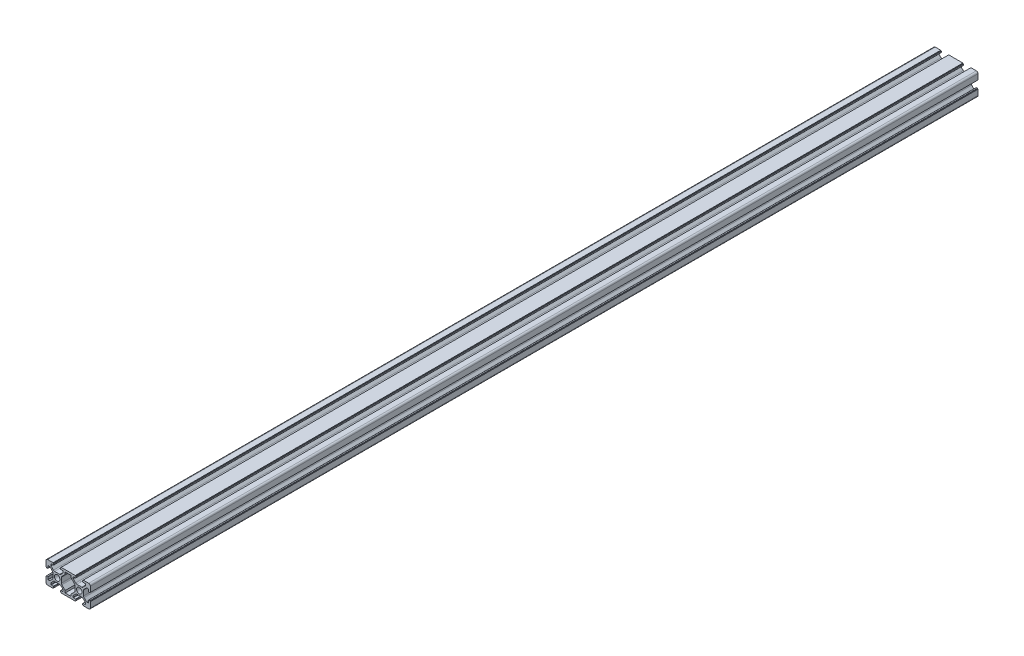
SolidWorks part; units mm, degrees
ref_plane "前视基准面" through (0, 0, 0) normal (0, 0, 1) x (1, 0, 0)
ref_plane "上视基准面" through (0, 0, 0) normal (0, 1, 0) x (1, 0, 0)
ref_plane "右视基准面" through (0, 0, 0) normal (1, 0, 0) x (0, 0, -1)
sketch "草图1" plane through (0, 0, 0) normal (0, 0, 1) x (1, 0, 0)
  line L0 (-1.9716, -6.6942) -> (-4.9322, -3.7335)
  line L1 (-5.3716, -2.6729) -> (-5.3716, 1.7645)
  line L2 (-4.9322, 2.8251) -> (-1.9716, 5.7858)
  line L3 (-0.7716, 9.5458) -> (-5.6716, 9.5458)
  line L4 (-5.6716, 9.5458) -> (-5.6716, 9.2458)
  line L5 (-5.8716, 9.0458) -> (-6.1716, 9.0458)
  line L6 (-6.1716, 9.0458) -> (-6.1716, 8.0458)
  line L7 (-5.8716, 7.7458) -> (-4.0716, 7.7458)
  line L8 (-3.7716, 7.4458) -> (-3.7716, 6.1058)
  line L9 (-3.7716, 6.1058) -> (-5.9922, 3.8851)
  line L10 (-7.0529, 3.4458) -> (-11.4903, 3.4458)
  line L11 (-12.5509, 3.8851) -> (-14.7716, 6.1058)
  line L12 (-14.7716, 6.1058) -> (-14.7716, 7.4458)
  line L13 (-14.4716, 7.7458) -> (-12.6716, 7.7458)
  line L14 (-12.3716, 8.0458) -> (-12.3716, 9.0458)
  line L15 (-12.3716, 9.0458) -> (-12.6716, 9.0458)
  line L16 (-12.8716, 9.2458) -> (-12.8716, 9.5458)
  line L17 (-12.8716, 9.5458) -> (-17.7716, 9.5458)
  line L18 (-19.2716, 8.0458) -> (-19.2716, 3.1458)
  line L19 (-19.2716, 3.1458) -> (-18.9716, 3.1458)
  line L20 (-18.7716, 2.9458) -> (-18.7716, 2.6458)
  line L21 (-18.7716, 2.6458) -> (-17.7716, 2.6458)
  line L22 (-17.4716, 2.9458) -> (-17.4716, 4.7458)
  line L23 (-17.1716, 5.0458) -> (-15.8316, 5.0458)
  line L24 (-15.8316, 5.0458) -> (-13.6109, 2.8251)
  line L25 (-13.1716, 1.7645) -> (-13.1716, -2.6729)
  line L26 (-13.6109, -3.7335) -> (-15.8316, -5.9542)
  line L27 (-15.8316, -5.9542) -> (-17.1716, -5.9542)
  line L28 (-17.4716, -5.6542) -> (-17.4716, -3.8542)
  line L29 (-17.7716, -3.5542) -> (-18.7716, -3.5542)
  line L30 (-18.7716, -3.5542) -> (-18.7716, -3.8542)
  line L31 (-18.9716, -4.0542) -> (-19.2716, -4.0542)
  line L32 (-19.2716, -4.0542) -> (-19.2716, -8.9542)
  line L33 (-17.7716, -10.4542) -> (-12.8716, -10.4542)
  line L34 (-12.8716, -10.4542) -> (-12.8716, -10.1542)
  line L35 (-12.6716, -9.9542) -> (-12.3716, -9.9542)
  line L36 (-12.3716, -9.9542) -> (-12.3716, -8.9542)
  line L37 (-12.6716, -8.6542) -> (-14.4716, -8.6542)
  line L38 (-14.7716, -8.3542) -> (-14.7716, -7.0142)
  line L39 (-14.7716, -7.0142) -> (-12.5509, -4.7935)
  line L40 (-11.4903, -4.3542) -> (-7.0529, -4.3542)
  line L41 (-5.9922, -4.7935) -> (-3.7716, -7.0142)
  line L42 (-3.7716, -7.0142) -> (-3.7716, -8.3542)
  line L43 (-4.0716, -8.6542) -> (-5.8716, -8.6542)
  line L44 (-6.1716, -8.9542) -> (-6.1716, -9.9542)
  line L45 (-6.1716, -9.9542) -> (-5.8716, -9.9542)
  line L46 (-5.6716, -10.1542) -> (-5.6716, -10.4542)
  line L47 (-5.6716, -10.4542) -> (-0.7716, -10.4542)
  line L48 (-0.7716, -10.4542) -> (7.1284, -10.4542)
  line L49 (7.1284, -10.4542) -> (7.1284, -10.1542)
  line L50 (7.3284, -9.9542) -> (7.6284, -9.9542)
  line L51 (7.6284, -9.9542) -> (7.6284, -8.9542)
  line L52 (7.3284, -8.6542) -> (5.5284, -8.6542)
  line L53 (5.2284, -8.3542) -> (5.2284, -7.0142)
  line L54 (5.2284, -7.0142) -> (7.4491, -4.7935)
  line L55 (8.5097, -4.3542) -> (12.9471, -4.3542)
  line L56 (14.0078, -4.7935) -> (16.2284, -7.0142)
  line L57 (16.2284, -7.0142) -> (16.2284, -8.3542)
  line L58 (15.9284, -8.6542) -> (14.1284, -8.6542)
  line L59 (13.8284, -8.9542) -> (13.8284, -9.9542)
  line L60 (13.8284, -9.9542) -> (14.1284, -9.9542)
  line L61 (14.3284, -10.1542) -> (14.3284, -10.4542)
  line L62 (14.3284, -10.4542) -> (19.2284, -10.4542)
  line L63 (20.7284, -8.9542) -> (20.7284, -4.0542)
  line L64 (20.7284, -4.0542) -> (20.4284, -4.0542)
  line L65 (20.2284, -3.8542) -> (20.2284, -3.5542)
  line L66 (20.2284, -3.5542) -> (19.2284, -3.5542)
  line L67 (18.9284, -3.8542) -> (18.9284, -5.6542)
  line L68 (18.6284, -5.9542) -> (17.2884, -5.9542)
  line L69 (17.2884, -5.9542) -> (15.0678, -3.7335)
  line L70 (14.6284, -2.6729) -> (14.6284, 1.7645)
  line L71 (15.0678, 2.8251) -> (17.2884, 5.0458)
  line L72 (17.2884, 5.0458) -> (18.6284, 5.0458)
  line L73 (18.9284, 4.7458) -> (18.9284, 2.9458)
  line L74 (19.2284, 2.6458) -> (20.2284, 2.6458)
  line L75 (20.2284, 2.6458) -> (20.2284, 2.9458)
  line L76 (20.4284, 3.1458) -> (20.7284, 3.1458)
  line L77 (20.7284, 3.1458) -> (20.7284, 8.0458)
  line L78 (19.2284, 9.5458) -> (14.3284, 9.5458)
  line L79 (14.3284, 9.5458) -> (14.3284, 9.2458)
  line L80 (14.1284, 9.0458) -> (13.8284, 9.0458)
  line L81 (13.8284, 9.0458) -> (13.8284, 8.0458)
  line L82 (14.1284, 7.7458) -> (15.9284, 7.7458)
  line L83 (16.2284, 7.4458) -> (16.2284, 6.1058)
  line L84 (16.2284, 6.1058) -> (14.0078, 3.8851)
  line L85 (12.9471, 3.4458) -> (8.5097, 3.4458)
  line L86 (7.4491, 3.8851) -> (5.2284, 6.1058)
  line L87 (5.2284, 6.1058) -> (5.2284, 7.4458)
  line L88 (5.5284, 7.7458) -> (7.3284, 7.7458)
  line L89 (7.6284, 8.0458) -> (7.6284, 9.0458)
  line L90 (7.6284, 9.0458) -> (7.3284, 9.0458)
  line L91 (7.1284, 9.2458) -> (7.1284, 9.5458)
  line L92 (7.1284, 9.5458) -> (2.2284, 9.5458)
  line L93 (3.4284, 5.7858) -> (6.3891, 2.8251)
  line L94 (6.8284, 1.7645) -> (6.8284, -2.6729)
  line L95 (6.3891, -3.7335) -> (3.4284, -6.6942)
  line L96 (-0.7716, 9.5458) -> (2.2284, 9.5458)
  line L99 (-1.9716, 7.7458) -> (3.4284, 7.7458)
  line L100 (3.4284, 7.7458) -> (3.4284, 5.7858)
  line L101 (-1.9716, 7.7458) -> (-1.9716, 5.7858)
  line L102 (-1.9716, -8.6542) -> (3.4284, -8.6542)
  line L103 (3.4284, -8.6542) -> (3.4284, -6.6942)
  line L104 (-1.9716, -8.6542) -> (-1.9716, -6.6942)
  arc A1 (-5.3716, -2.6729) -> (-4.9322, -3.7335) centre (-3.8716, -2.6729) ccw
  arc A2 (-4.9322, 2.8251) -> (-5.3716, 1.7645) centre (-3.8716, 1.7645) ccw
  arc A3 (-5.8716, 9.0458) -> (-5.6716, 9.2458) centre (-5.8716, 9.2458) ccw
  arc A4 (-6.1716, 8.0458) -> (-5.8716, 7.7458) centre (-5.8716, 8.0458) ccw
  arc A5 (-3.7716, 7.4458) -> (-4.0716, 7.7458) centre (-4.0716, 7.4458) ccw
  arc A6 (-7.0529, 3.4458) -> (-5.9922, 3.8851) centre (-7.0529, 4.9458) ccw
  arc A7 (-12.5509, 3.8851) -> (-11.4903, 3.4458) centre (-11.4903, 4.9458) ccw
  arc A8 (-14.4716, 7.7458) -> (-14.7716, 7.4458) centre (-14.4716, 7.4458) ccw
  arc A9 (-12.6716, 7.7458) -> (-12.3716, 8.0458) centre (-12.6716, 8.0458) ccw
  arc A10 (-12.8716, 9.2458) -> (-12.6716, 9.0458) centre (-12.6716, 9.2458) ccw
  arc A11 (-17.7716, 9.5458) -> (-19.2716, 8.0458) centre (-17.7716, 8.0458) ccw
  arc A12 (-18.7716, 2.9458) -> (-18.9716, 3.1458) centre (-18.9716, 2.9458) ccw
  arc A13 (-17.7716, 2.6458) -> (-17.4716, 2.9458) centre (-17.7716, 2.9458) ccw
  arc A14 (-17.1716, 5.0458) -> (-17.4716, 4.7458) centre (-17.1716, 4.7458) ccw
  arc A15 (-13.1716, 1.7645) -> (-13.6109, 2.8251) centre (-14.6716, 1.7645) ccw
  arc A16 (-13.6109, -3.7335) -> (-13.1716, -2.6729) centre (-14.6716, -2.6729) ccw
  arc A17 (-17.4716, -5.6542) -> (-17.1716, -5.9542) centre (-17.1716, -5.6542) ccw
  arc A18 (-17.4716, -3.8542) -> (-17.7716, -3.5542) centre (-17.7716, -3.8542) ccw
  arc A19 (-18.9716, -4.0542) -> (-18.7716, -3.8542) centre (-18.9716, -3.8542) ccw
  arc A20 (-19.2716, -8.9542) -> (-17.7716, -10.4542) centre (-17.7716, -8.9542) ccw
  arc A21 (-12.6716, -9.9542) -> (-12.8716, -10.1542) centre (-12.6716, -10.1542) ccw
  arc A22 (-12.3716, -8.9542) -> (-12.6716, -8.6542) centre (-12.6716, -8.9542) ccw
  arc A23 (-14.7716, -8.3542) -> (-14.4716, -8.6542) centre (-14.4716, -8.3542) ccw
  arc A24 (-11.4903, -4.3542) -> (-12.5509, -4.7935) centre (-11.4903, -5.8542) ccw
  arc A25 (-5.9922, -4.7935) -> (-7.0529, -4.3542) centre (-7.0529, -5.8542) ccw
  arc A26 (-4.0716, -8.6542) -> (-3.7716, -8.3542) centre (-4.0716, -8.3542) ccw
  arc A27 (-5.8716, -8.6542) -> (-6.1716, -8.9542) centre (-5.8716, -8.9542) ccw
  arc A28 (-5.6716, -10.1542) -> (-5.8716, -9.9542) centre (-5.8716, -10.1542) ccw
  arc A29 (7.3284, -9.9542) -> (7.1284, -10.1542) centre (7.3284, -10.1542) ccw
  arc A30 (7.6284, -8.9542) -> (7.3284, -8.6542) centre (7.3284, -8.9542) ccw
  arc A31 (5.2284, -8.3542) -> (5.5284, -8.6542) centre (5.5284, -8.3542) ccw
  arc A32 (8.5097, -4.3542) -> (7.4491, -4.7935) centre (8.5097, -5.8542) ccw
  arc A33 (14.0078, -4.7935) -> (12.9471, -4.3542) centre (12.9471, -5.8542) ccw
  arc A34 (15.9284, -8.6542) -> (16.2284, -8.3542) centre (15.9284, -8.3542) ccw
  arc A35 (14.1284, -8.6542) -> (13.8284, -8.9542) centre (14.1284, -8.9542) ccw
  arc A36 (14.3284, -10.1542) -> (14.1284, -9.9542) centre (14.1284, -10.1542) ccw
  arc A37 (19.2284, -10.4542) -> (20.7284, -8.9542) centre (19.2284, -8.9542) ccw
  arc A38 (20.2284, -3.8542) -> (20.4284, -4.0542) centre (20.4284, -3.8542) ccw
  arc A39 (19.2284, -3.5542) -> (18.9284, -3.8542) centre (19.2284, -3.8542) ccw
  arc A40 (18.6284, -5.9542) -> (18.9284, -5.6542) centre (18.6284, -5.6542) ccw
  arc A41 (14.6284, -2.6729) -> (15.0678, -3.7335) centre (16.1284, -2.6729) ccw
  arc A42 (15.0678, 2.8251) -> (14.6284, 1.7645) centre (16.1284, 1.7645) ccw
  arc A43 (18.9284, 4.7458) -> (18.6284, 5.0458) centre (18.6284, 4.7458) ccw
  arc A44 (18.9284, 2.9458) -> (19.2284, 2.6458) centre (19.2284, 2.9458) ccw
  arc A45 (20.4284, 3.1458) -> (20.2284, 2.9458) centre (20.4284, 2.9458) ccw
  arc A46 (20.7284, 8.0458) -> (19.2284, 9.5458) centre (19.2284, 8.0458) ccw
  arc A47 (14.1284, 9.0458) -> (14.3284, 9.2458) centre (14.1284, 9.2458) ccw
  arc A48 (13.8284, 8.0458) -> (14.1284, 7.7458) centre (14.1284, 8.0458) ccw
  arc A49 (16.2284, 7.4458) -> (15.9284, 7.7458) centre (15.9284, 7.4458) ccw
  arc A50 (12.9471, 3.4458) -> (14.0078, 3.8851) centre (12.9471, 4.9458) ccw
  arc A51 (7.4491, 3.8851) -> (8.5097, 3.4458) centre (8.5097, 4.9458) ccw
  arc A52 (5.5284, 7.7458) -> (5.2284, 7.4458) centre (5.5284, 7.4458) ccw
  arc A53 (7.3284, 7.7458) -> (7.6284, 8.0458) centre (7.3284, 8.0458) ccw
  arc A54 (7.1284, 9.2458) -> (7.3284, 9.0458) centre (7.3284, 9.2458) ccw
  arc A55 (6.8284, 1.7645) -> (6.3891, 2.8251) centre (5.3284, 1.7645) ccw
  arc A56 (6.3891, -3.7335) -> (6.8284, -2.6729) centre (5.3284, -2.6729) ccw
  circle A58 centre (10.7284, -0.4542) radius 2.5
  circle A63 centre (-9.2716, -0.4542) radius 2.5
extrude "凸台-拉伸1" add sketch "草图1" along normal blind 800
